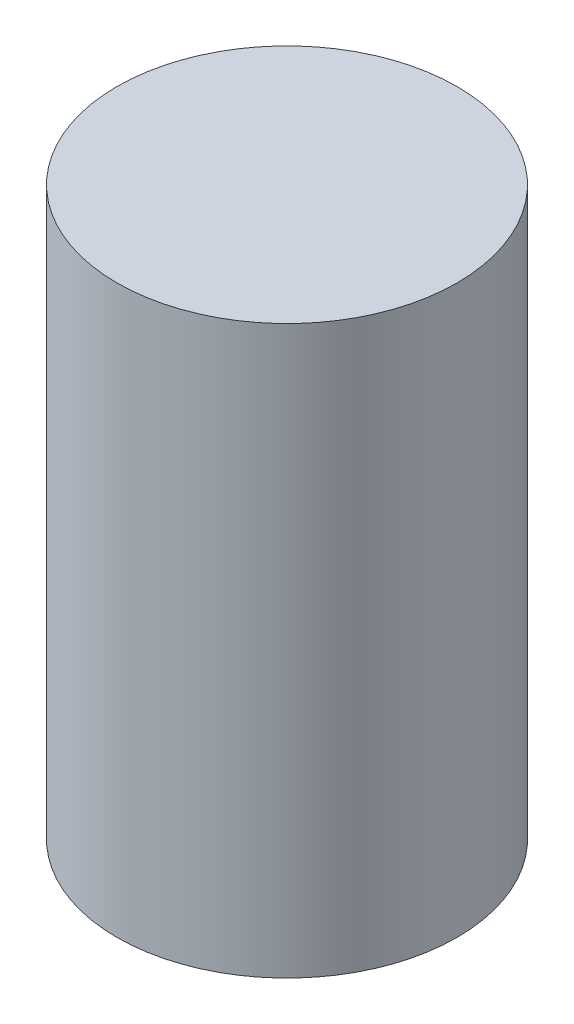
SolidWorks part; units mm, degrees
ref_plane "Alzado" through (0, 0, 0) normal (0, 0, 1) x (1, 0, 0)
ref_plane "Planta" through (0, 0, 0) normal (0, 1, 0) x (1, 0, 0)
ref_plane "Vista lateral" through (0, 0, 0) normal (1, 0, 0) x (0, 0, -1)
sketch "Sketch1" plane through (0, 0, 0) normal (0, 1, 0) x (1, 0, 0)
  circle A0 centre (0, 0) radius 3
  dimension "D1" = 6
extrude "Boss-Extrude1" add sketch "Sketch1" along normal blind 10
